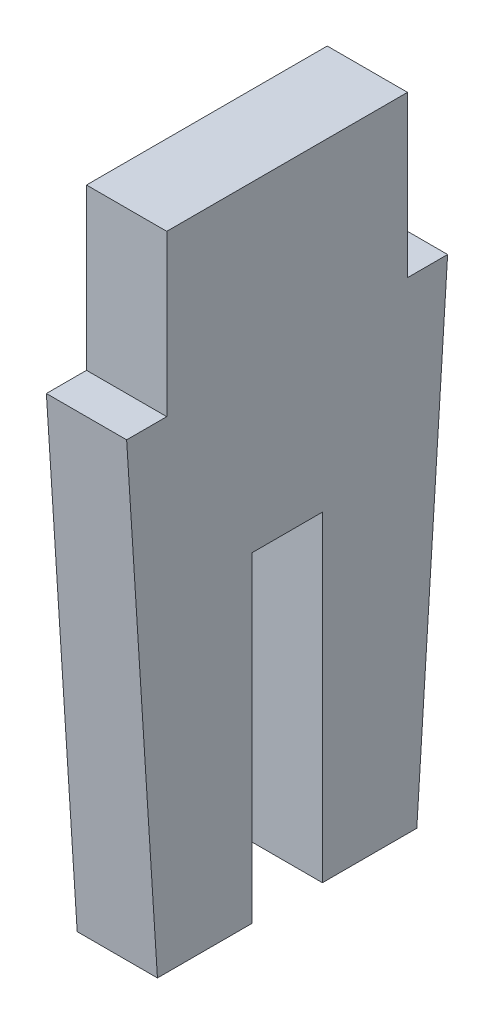
SolidWorks part; units mm, degrees
ref_plane "Front Plane" through (0, 0, 0) normal (0, 0, 1) x (1, 0, 0)
ref_plane "Top Plane" through (0, 0, 0) normal (0, 1, 0) x (1, 0, 0)
ref_plane "Right Plane" through (0, 0, 0) normal (1, 0, 0) x (0, 0, -1)
sketch "Sketch1" plane through (0, 0, 0) normal (1, 0, 0) x (0, 0, -1)
  line L0 (0, 55) -> (0, -55) construction
  line L1 (0, 50.8) -> (19.05, 50.8)
  line L2 (0, 50.8) -> (0, 38.1)
  line L3 (-3.175, 38.1) -> (22.225, 38.1) construction
  line L4 (19.05, 50.8) -> (19.05, 38.1)
  line L5 (0, 38.1) -> (-3.175, 38.1)
  line L6 (9.525, 38.1) -> (9.525, 6.35) construction
  line L7 (19.05, 38.1) -> (22.225, 38.1)
  line L8 (-1.143, 6.35) -> (20.193, 6.35) construction
  line L9 (-3.175, 38.1) -> (-1.143, 6.35)
  line L10 (22.225, 38.1) -> (20.193, 6.35)
  line L11 (20.193, 6.35) -> (19.7866, 0)
  line L12 (-1.143, 6.35) -> (-0.7366, 0)
  line L13 (-0.7366, 0) -> (6.731, 0)
  line L14 (55, 0) -> (-55, 0) construction
  line L15 (12.319, 0) -> (19.7866, 0)
  line L16 (12.319, 25.4) -> (6.731, 25.4)
  line L17 (12.319, 25.4) -> (12.319, 0)
  line L19 (6.731, 25.4) -> (6.731, 0)
  line L20 (12.319, 25.4) -> (6.731, 0) construction
  line L21 (12.319, 0) -> (6.731, 25.4) construction
  point P8 (9.525, 12.7)
  dimension "D1" = 12.7
  dimension "D2" = 19.05
  dimension "D3" = 25.4
  dimension "D4" = 31.75
  dimension "D5" = 21.336
  dimension "D6" = 6.35
  dimension "D7" = 20.5232
  dimension "D8" = 20.5232
  dimension "D9" = 5.588
  dimension "D10" = 25.4
  dimension "D11" = 50.8
extrude "Boss-Extrude1" add sketch "Sketch1" along normal blind 6.35
